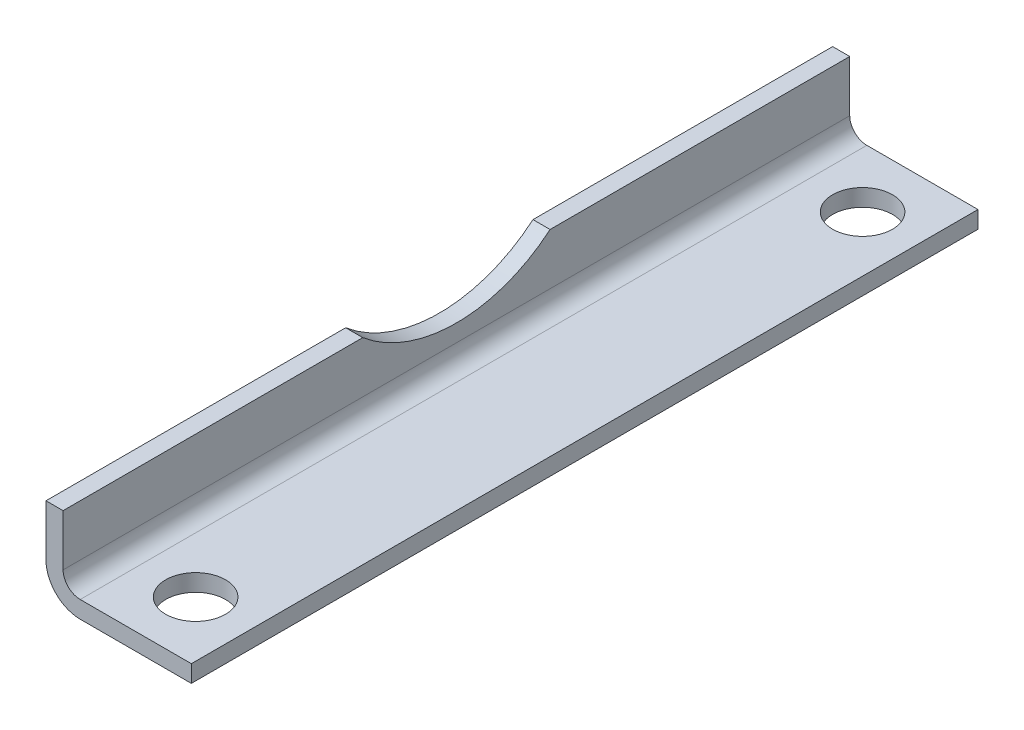
SolidWorks part; units mm, degrees
material "AISI 1010 钢，热轧条材"
ref_plane "前视基准面" through (0, 0, 0) normal (0, 0, 1) x (1, 0, 0)
ref_plane "上视基准面" through (0, 0, 0) normal (0, 1, 0) x (1, 0, 0)
ref_plane "右视基准面" through (0, 0, 0) normal (1, 0, 0) x (0, 0, -1)
sketch "草图1" plane through (0, 0, 0) normal (0, 0, 1) x (1, 0, 0)
  line L0 (0, 0) -> (0, 10)
  line L1 (0, 0) -> (17, 0)
  line L2 (17, 0) -> (17, 2)
  line L3 (17, 2) -> (2, 2)
  line L4 (2, 2) -> (2, 10)
  line L5 (2, 10) -> (0, 10)
  dimension "D1" = 17
  dimension "D2" = 10
  dimension "D3" = 2
  dimension "D4" = 2
extrude "凸台-拉伸1" add sketch "草图1" along normal mid plane 92
fillet "圆角1" radius 4 1 edges at (0, 0, 0)
fillet "圆角2" radius 2 1 edges at (2, 2, 0)
sketch "草图2" plane through (0, 0, 0) normal (0, -1, 0) x (1, 0, 0)
  line L0 (10.5, 46) -> (10.5, -46) construction
  line L1 (4, 46) -> (17, 46) construction
  line L2 (4, -46) -> (17, -46) construction
  line L3 (17, 46) -> (17, -46) construction
  line L4 (0, 0) -> (50000, 0) construction
  circle A0 centre (10.5, 39) radius 3.5
  circle A1 centre (10.5, -39) radius 3.5
  dimension "D1" = 7
  dimension "D3" = 78
  dimension "D2" = 6.5
extrude "切除-拉伸1" cut sketch "草图2" against normal blind 10
sketch "草图3" plane through (0, 0, 0) normal (-1, 0, 0) x (0, 0, 1)
  line L0 (0, 0) -> (0, 40.9155) construction
  circle A0 centre (0, 23) radius 17
  dimension "D1" = 34
  dimension "D2" = 23
extrude "切除-拉伸2" cut sketch "草图3" against normal blind 10
